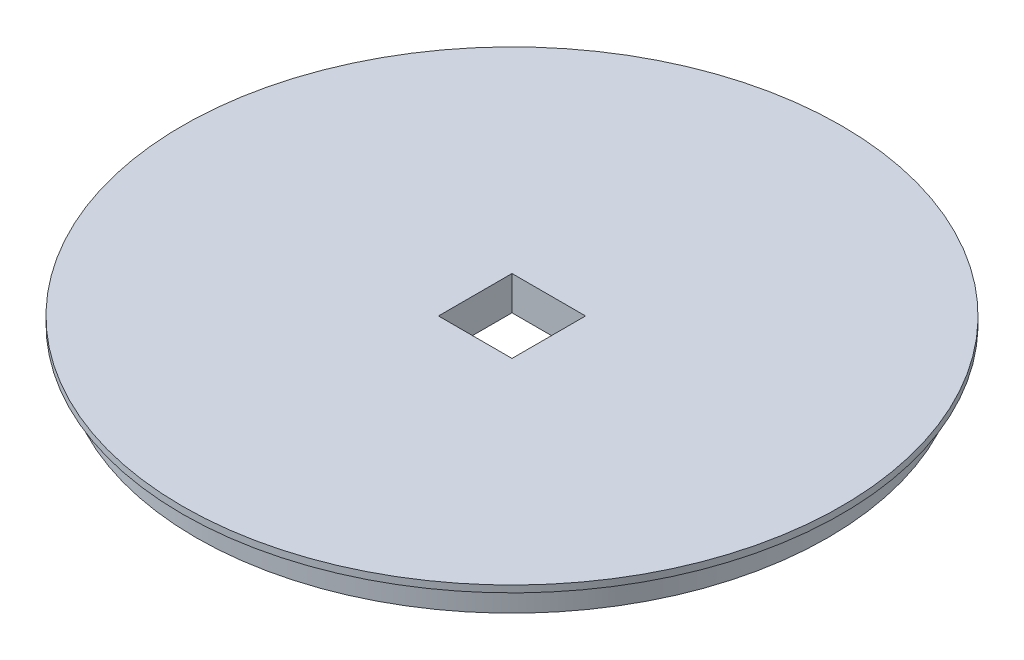
SolidWorks part; units mm, degrees
ref_plane "Front Plane" through (0, 0, 0) normal (0, 0, 1) x (1, 0, 0)
ref_plane "Top Plane" through (0, 0, 0) normal (0, 1, 0) x (1, 0, 0)
ref_plane "Right Plane" through (0, 0, 0) normal (1, 0, 0) x (0, 0, -1)
sketch "Sketch1" plane through (0, 0, 0) normal (0, 0, 1) x (1, 0, 0)
  line L0 (0, 0) -> (0, 3.175) construction
  line L1 (0, 3.175) -> (-30.734, 3.175)
  line L2 (-30.734, 3.175) -> (-30.734, 2.54)
  line L3 (-30.734, 2.54) -> (-29.464, 2.54)
  line L4 (-29.464, 2.54) -> (-29.464, 0)
  line L5 (-29.464, 0) -> (0, 0)
  line L6 (0, 0) -> (0, 3.175)
  dimension "D1" = 29.464
  dimension "D2" = 2.54
  dimension "D3" = 1.27
  dimension "D4" = 3.175
revolve "Revolve1" add sketch "Sketch1" angle 360 about L0
sketch "Sketch2" plane through (0, 3.175, 0) normal (0, 1, 0) x (1, 0, 0)
  line L1 (-3.429, -3.429) -> (3.429, -3.429)
  line L2 (-3.429, -3.429) -> (-3.429, 3.429)
  line L3 (-3.429, 3.429) -> (3.429, 3.429)
  line L4 (3.429, -3.429) -> (3.429, 3.429)
  line L5 (-3.429, -3.429) -> (3.429, 3.429) construction
  line L6 (-3.429, 3.429) -> (3.429, -3.429) construction
  point P0 (0, 0)
  dimension "D1" = 6.858
extrude "Cut-Extrude1" cut sketch "Sketch2" against normal through all
